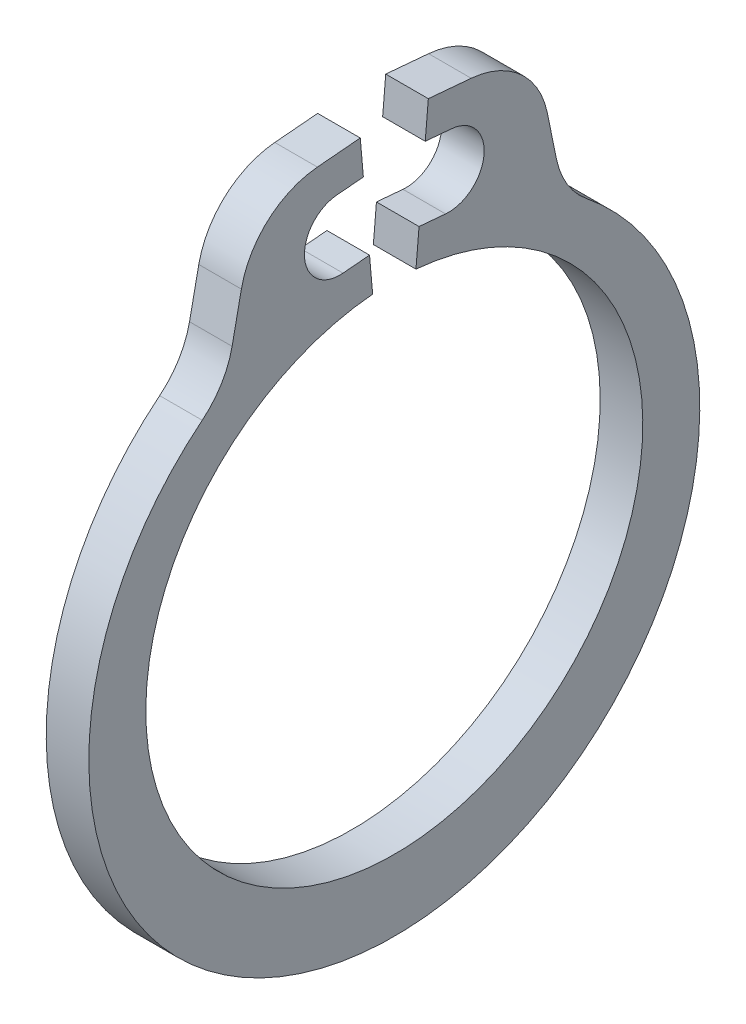
SolidWorks part; units mm, degrees
material "Cast Carbon Steel"
ref_plane "Front" through (0, 0, 0) normal (0, 0, 1) x (1, 0, 0)
ref_plane "Top" through (0, 0, 0) normal (0, 1, 0) x (1, 0, 0)
ref_plane "Right" through (0, 0, 0) normal (1, 0, 0) x (0, 0, -1)
sketch "Sketch1" plane through (0, 0, 0) normal (1, 0, 0) x (0, 0, -1)
  line L0 (0, 0) -> (0, 2.2225) construction
  line L1 (-0.1937, 2.214) -> (-0.3044, 3.4792) construction
  line L2 (0.3044, 3.4792) -> (1.2533, 3.3962)
  line L3 (1.2533, 3.3962) -> (1.5095, 2.1523)
  line L4 (0.1937, 2.214) -> (0.3044, 3.4792) construction
  line L5 (-0.3044, 3.4792) -> (-1.2533, 3.3962)
  line L6 (-1.2533, 3.3962) -> (-1.5095, 2.1523)
  line L7 (-1.5095, 2.1523) -> (-1.2762, 1.8196) construction
  line L8 (1.5095, 2.1523) -> (1.2762, 1.8196) construction
  line L9 (0, -2.2225) -> (0, -2.8575) construction
  line L10 (-1.2533, 3.3962) -> (-0.1937, 2.214) construction
  line L11 (0, 2.2225) -> (0, 3.4925) construction
  line L12 (0.2214, 2.5303) -> (0.4586, 2.5096)
  line L13 (0.2767, 3.1629) -> (0.5139, 3.1422)
  line L14 (0.2214, 2.5303) -> (0.1937, 2.214)
  line L15 (0.2767, 3.1629) -> (0.3044, 3.4792)
  line L16 (-0.2767, 3.1629) -> (-0.5139, 3.1422)
  line L17 (-0.2214, 2.5303) -> (-0.4586, 2.5096)
  line L18 (-0.2214, 2.5303) -> (-0.1937, 2.214)
  line L19 (-0.2767, 3.1629) -> (-0.3044, 3.4792)
  line L20 (-2.2225, 0) -> (2.2225, 0) construction
  circle A0 centre (0, 0) radius 2.2225 construction
  arc A1 (-0.1937, 2.214) -> (0.1937, 2.214) centre (0, 0) ccw
  arc A2 (0.4586, 2.5096) -> (0.5139, 3.1422) centre (0.4863, 2.8259) ccw
  circle A3 centre (0, 0) radius 3.6322 construction
  arc A4 (-0.4586, 2.5096) -> (-0.5139, 3.1422) centre (-0.4863, 2.8259) cw
  arc A6 (-1.5095, 2.1523) -> (1.5095, 2.1523) centre (0, -0.1252) ccw
  point P0 (0, -2.8575)
  dimension "A" = 4.445
  dimension "Smin" = 0.4064
  dimension "H" = 1.27
  dimension "D2" = 0.9525
  dimension "Angle" = 5
  dimension "R" = 0.635
extrude "Extrude1" add sketch "Sketch1" along normal mid plane 0.381
fillet "Fillet1" radius 0.762 4 edges at (0, 2.1523, 1.5095) (0, 2.1523, -1.5095) (0, 3.3962, 1.2533) (0, 3.3962, -1.2533)
sketch "Sketch2" plane through (0, 0, 0) normal (0, 0, 1) x (1, 0, 0)
  line L0 (-2.1336, 0) -> (5.4864, 0)
  line L1 (5.4864, 0) -> (5.4864, -2.3876)
  line L2 (-0.2286, -2.3876) -> (-1.9685, -2.3876)
  line L3 (5.4864, -2.3876) -> (0.2286, -2.3876)
  line L4 (0.2286, -2.3876) -> (0.2286, -2.2225)
  line L5 (0.2286, -2.2225) -> (-0.2286, -2.2225)
  line L6 (-0.2286, -2.2225) -> (-0.2286, -2.3876)
  line L7 (-0.2286, -2.3876) -> (-2.1336, -2.3876) construction
  line L8 (-2.1336, -2.3876) -> (-2.1336, 0) construction
  line L9 (5.4864, 0) -> (76.391, 0) construction
  line L10 (-1.9685, -2.3876) -> (-2.1336, -2.2225)
  line L11 (-2.1336, -2.2225) -> (-2.1336, 0)
  point P10 (0, -2.2225)
  dimension "D2" = 7.62
  dimension "D3" = 1.905
  dimension "D1" = 45
revolve "Revolve1" [suppressed] add sketch "Sketch2" angle 360 about L9
delete or keep bodies "Body-Delete1" [suppressed] type delete bodies bodies 122
equation "\"D2@Sketch2\" = \"D1@Extrude1\"*20"
equation "\"D3@Sketch2\" = \"D2@Sketch2\"/4"
equation "\"D2@Sketch1\" = \"H@Sketch1\"*.75"
equation "\"D1@Fillet1\" = \"D1@Extrude1\"*2"
